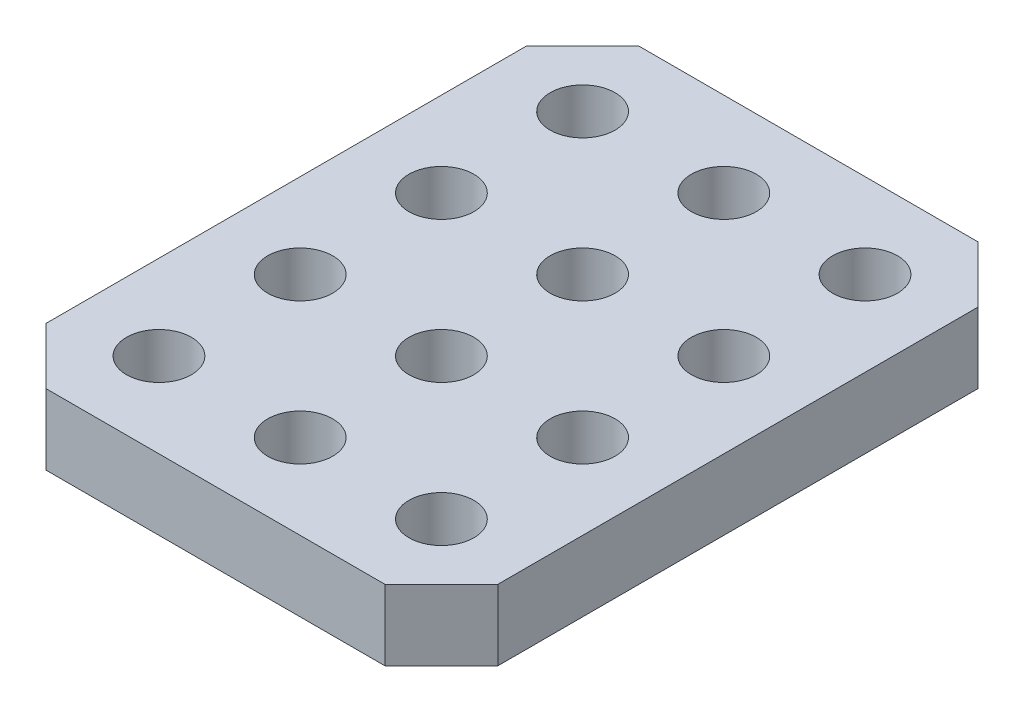
SolidWorks part; units mm, degrees
ref_plane "Front Plane" through (0, 0, 0) normal (0, 0, 1) x (1, 0, 0)
ref_plane "Top Plane" through (0, 0, 0) normal (0, 1, 0) x (1, 0, 0)
ref_plane "Right Plane" through (0, 0, 0) normal (1, 0, 0) x (0, 0, -1)
sketch "Sketch1" plane through (0, 0, 0) normal (0, 1, 0) x (1, 0, 0)
  line L0 (0, 48.26) -> (5.08, 53.34)
  line L1 (5.08, 0) -> (35.56, 0)
  line L2 (0, 5.08) -> (0, 48.26)
  line L3 (5.08, 53.34) -> (35.56, 53.34)
  line L4 (40.64, 5.08) -> (40.64, 48.26)
  line L5 (35.56, 53.34) -> (40.64, 48.26)
  line L6 (35.56, 0) -> (40.64, 5.08)
  line L7 (0, 5.08) -> (5.08, 0)
  circle A0 centre (7.62, 7.62) radius 2.921
  circle A7 centre (20.32, 7.62) radius 2.921
  circle A8 centre (33.02, 7.62) radius 2.921
  circle A9 centre (20.32, 20.32) radius 2.921
  circle A10 centre (33.02, 20.32) radius 2.921
  circle A11 centre (20.32, 33.02) radius 2.921
  circle A12 centre (33.02, 33.02) radius 2.921
  circle A13 centre (20.32, 45.72) radius 2.921
  circle A14 centre (33.02, 45.72) radius 2.921
  circle A15 centre (7.62, 20.32) radius 2.921
  circle A16 centre (7.62, 33.02) radius 2.921
  circle A17 centre (7.62, 45.72) radius 2.921
  point P0 (0, 0)
  point P1 (40.64, 53.34)
  point P2 (0, 53.34)
  point P3 (40.64, 0)
  dimension "D3" = 5.842
  dimension "D1" = 40.64
  dimension "D2" = 53.34
  dimension "D4" = 7.62
  dimension "D5" = 7.62
  dimension "D6" = 3
  dimension "D7" = 4
extrude "Boss-Extrude1" add sketch "Sketch1" along normal blind 6.35
